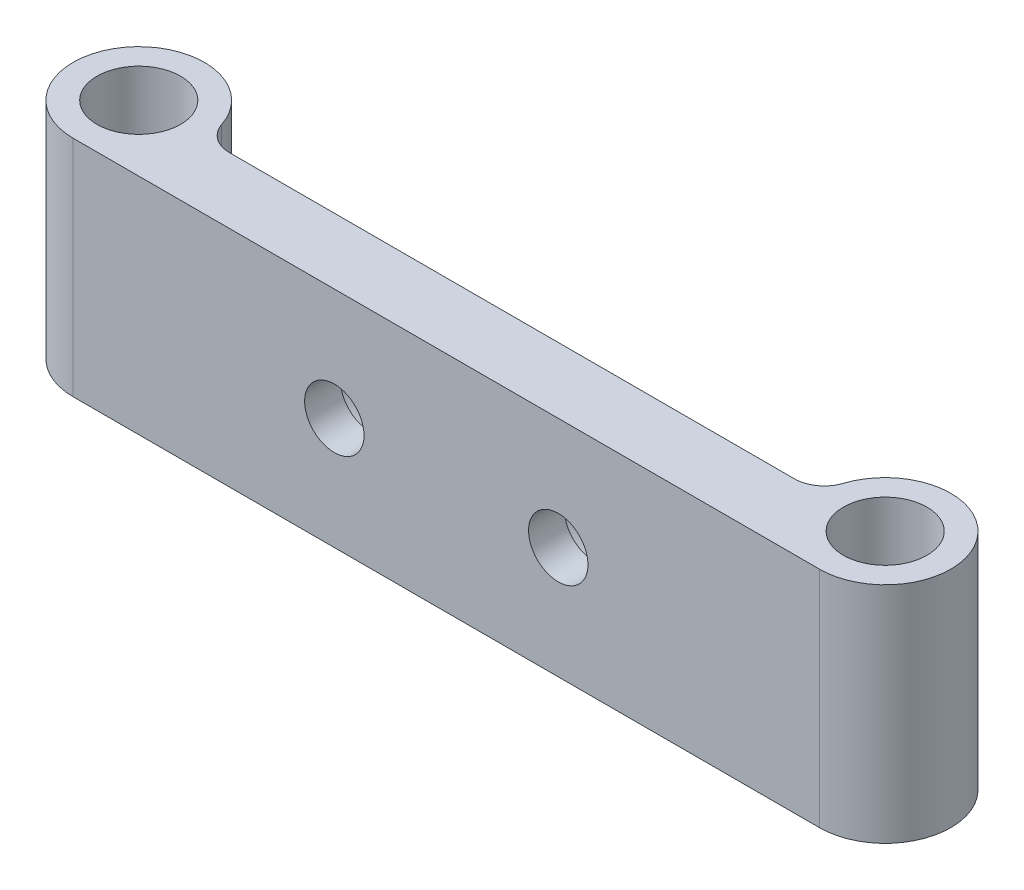
SolidWorks part; units mm, degrees
material "ABS"
ref_plane "Front Plane" through (0, 0, 0) normal (0, 0, 1) x (1, 0, 0)
ref_plane "Top Plane" through (0, 0, 0) normal (0, 1, 0) x (1, 0, 0)
ref_plane "Right Plane" through (0, 0, 0) normal (1, 0, 0) x (0, 0, -1)
sketch "Sketch1" plane through (0, 0, 0) normal (0, 1, 0) x (1, 0, 0)
  line L0 (-31.75, 0) -> (31.75, 0)
  line L1 (-26.162, 5.588) -> (26.162, 5.588)
  line L3 (-31.75, 11.176) -> (31.75, 11.176) construction
  arc A0 (31.75, 0) -> (26.162, 5.588) centre (31.75, 5.588) ccw
  arc A1 (-26.162, 5.588) -> (-31.75, 0) centre (-31.75, 5.588) ccw
  circle A2 centre (31.75, 5.588) radius 3.556
  circle A3 centre (-31.75, 5.588) radius 3.556
  point P3 (0, 0)
  dimension "D1" = 11.176
  dimension "D4" = 7.112
  dimension "D3" = 63.5
extrude "Boss-Extrude1" add sketch "Sketch1" along normal blind 19.05
fillet "Fillet2" radius 2.54 2 edges at (26.162, 9.525, -5.588) (-26.162, 9.525, -5.588)
hole_wizard "#8 (0.199) Diameter Hole1" positions "Sketch8" profile "Sketch9" hole size "#8" standard "ANSI Inch"
sketch "Sketch8" plane through (0, 0, 0) normal (0, 0, 1) x (1, 0, 0)
  line L0 (-9.525, 9.525) -> (9.525, 9.525)
  line L3 (31.75, 19.05) -> (31.75, 0) construction
  point P0 (-9.525, 9.525)
  point P2 (9.525, 9.525)
  point P8 (0, 9.525)
  point P15 (31.75, 9.525)
  dimension "D1" = 19.05
sketch "Sketch9" plane through (-9.525, 9.525, 0) normal (1, 0, 0) x (0, -1, 0)
  line L0 (0, 0) -> (0, 10.668)
  line L1 (0, 10.668) -> (2.5273, 9.1494)
  line L2 (2.5273, 9.1494) -> (2.5273, 0)
  line L5 (2.5273, 0) -> (0, 0)
  line L10 (0, 10.668) -> (-2.5273, 9.1494) construction
  line L11 (0, -6.35) -> (0, 107.95) construction
  dimension "Hole Dia." = 5.0546
  dimension "Hole Depth" = 10.668
  dimension "Drill Angle" = 118
sketch "Sketch10" plane through (0, 19.05, 0) normal (0, 1, 0) x (1, 0, 0)
  line L0 (-31.75, 5.588) -> (31.75, 5.588) construction
  circle A0 centre (0, 5.588) radius 44.45
  dimension "D1" = 88.9
sketch "Sketch11" plane through (0, 0, -5.588) normal (0, 0, -1) x (-1, 0, 0)
  circle A0 centre (-9.525, 9.525) radius 5.08
  circle A1 centre (9.525, 9.525) radius 5.08
  dimension "D1" = 10.16
extrude "Cut-Extrude1" cut sketch "Sketch11" against normal blind 2.54
